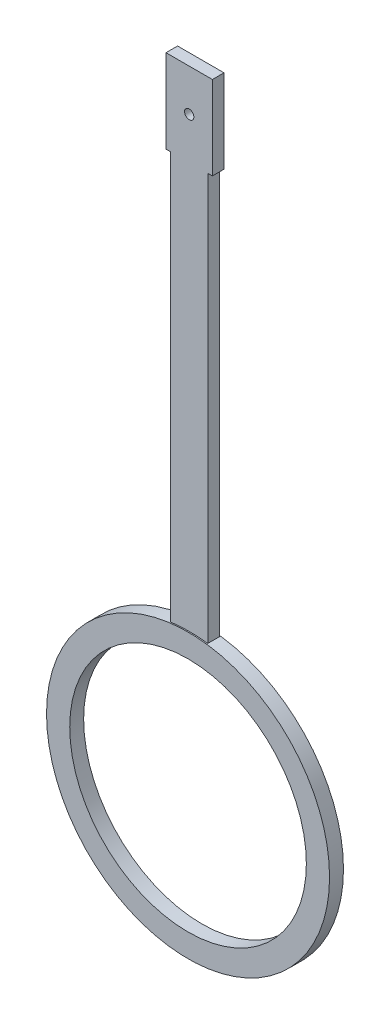
SolidWorks part; units mm, degrees
material "Gray Cast Iron"
ref_plane "Front Plane" through (0, 0, 0) normal (0, 0, 1) x (1, 0, 0)
ref_plane "Top Plane" through (0, 0, 0) normal (0, 1, 0) x (1, 0, 0)
ref_plane "Right Plane" through (0, 0, 0) normal (1, 0, 0) x (0, 0, -1)
sketch "Sketch1" plane through (0, 0, 0) normal (0, 0, 1) x (1, 0, 0)
  circle A0 centre (0, 0) radius 30.5
  dimension "D1" = 61
extrude "Boss-Extrude1" add sketch "Sketch1" along normal mid plane 3
sketch "Sketch2" plane through (0, 0, 0) normal (0, 0, 1) x (1, 0, 0)
  line L0 (-4, 25) -> (4, 25)
  line L1 (4, 25) -> (4, 118)
  line L2 (4, 118) -> (-4, 118)
  line L3 (-4, 118) -> (-4, 25)
  dimension "D1" = 8
  dimension "D2" = 93
  dimension "D3" = 4
  dimension "D4" = 25
extrude "Boss-Extrude2" add sketch "Sketch2" along normal mid plane 2.5
sketch "Sketch3" plane through (0, 0, 0) normal (0, 0, 1) x (1, 0, 0)
  line L0 (-5, 118) -> (5, 118)
  line L1 (5, 118) -> (5, 136)
  line L2 (5, 136) -> (-5, 136)
  line L3 (-5, 136) -> (-5, 118)
  dimension "D1" = 10
  dimension "D2" = 18
  dimension "D3" = 5
  dimension "D4" = 118
extrude "Boss-Extrude3" add sketch "Sketch3" along normal mid plane 2.5
sketch "Sketch4" plane through (0, 0, 0) normal (0, 0, 1) x (1, 0, 0)
  circle A0 centre (0, 0) radius 25.5
  dimension "D1" = 51
extrude "Cut-Extrude1" cut sketch "Sketch4" against normal mid plane 20
sketch "Sketch5" plane through (0, 0, 0) normal (0, 0, 1) x (1, 0, 0)
  circle A0 centre (0, 127) radius 1
  dimension "D2" = 2
  dimension "D1" = 127
extrude "Cut-Extrude2" cut sketch "Sketch5" against normal mid plane 20
